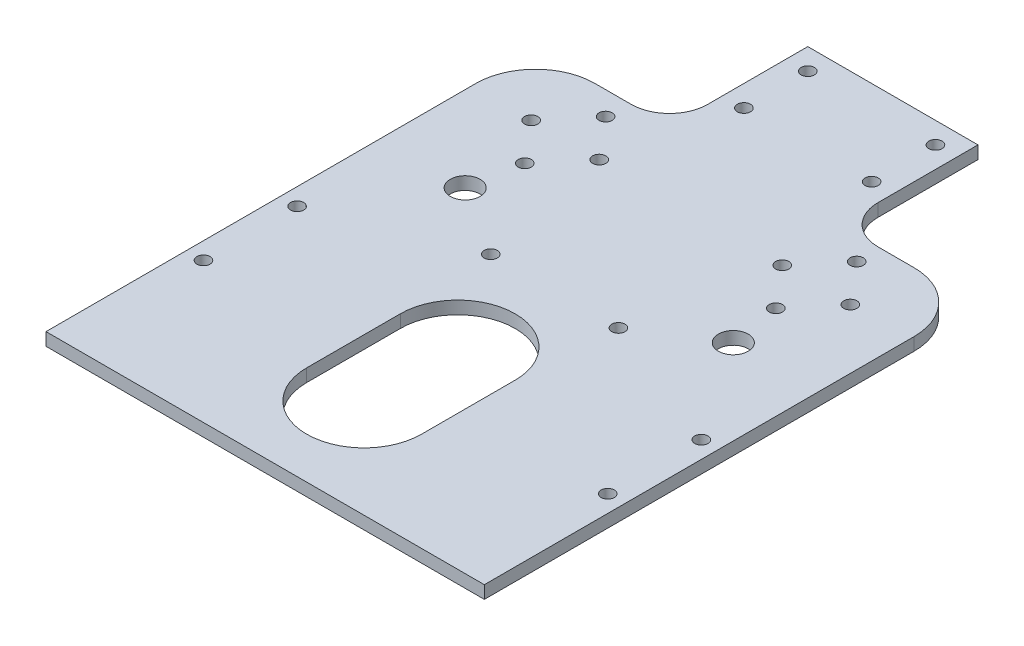
SolidWorks part; units mm, degrees
material "Hexcel AS4C (3000 丝)"
ref_plane "前视基准面" through (0, 0, 0) normal (0, 0, 1) x (1, 0, 0)
ref_plane "上视基准面" through (0, 0, 0) normal (0, 1, 0) x (1, 0, 0)
ref_plane "右视基准面" through (0, 0, 0) normal (1, 0, 0) x (0, 0, -1)
sketch "草图1" plane through (0, 0, 0) normal (0, 1, 0) x (1, 0, 0)
  line L1 (-100, 100) -> (100, 100)
  line L2 (-100, 100) -> (-100, -100)
  line L3 (-100, -100) -> (100, -100)
  line L4 (100, 100) -> (100, -100)
  line L5 (-100, 100) -> (100, -100) construction
  line L6 (-100, -100) -> (100, 100) construction
  point P0 (0, 0)
  dimension "D1" = 200
  dimension "D2" = 200
extrude "凸台-拉伸1" add sketch "草图1" along normal blind 3
sketch "草图2" plane through (0, 3, 0) normal (0, 1, 0) x (1, 0, 0)
  line L0 (0, 0) -> (0, 91) construction
  line L1 (-100, -100) -> (100, -100) construction
  line L2 (100, 100) -> (-100, 100) construction
  line L3 (-100, 0) -> (100, 0) construction
  line L5 (-100, 100) -> (-100, -100) construction
  line L6 (100, -100) -> (100, 100) construction
  line L7 (-29.5, 0) -> (29.5, 0) construction
  line L8 (-10, 100) -> (10, 100) construction
  line L9 (-10, 100) -> (-10, -100) construction
  line L10 (10, 100) -> (10, -100) construction
  line L11 (0, 0) -> (0, -29) construction
  line L13 (0, -29) -> (0, -32) construction
  circle A0 centre (-29.5, 0) radius 22.5 construction
  circle A1 centre (29.5, 0) radius 22.5 construction
  circle A2 centre (0, -29) radius 10.25 construction
  circle A3 centre (29.5, 0) radius 9.5 construction
  circle A4 centre (29.5, 0) radius 8 construction
  circle A5 centre (-29.5, 0) radius 8 construction
  circle A6 centre (-29.5, 0) radius 9.5 construction
  circle A7 centre (29.5, 9.5) radius 1.55
  circle A8 centre (21.5, 0) radius 1.55
  circle A9 centre (29.5, -9.5) radius 1.55
  circle A10 centre (37.5, 0) radius 1.55
  circle A11 centre (-29.5, -9.5) radius 1.55
  circle A12 centre (-37.5, 0) radius 1.55
  circle A13 centre (-21.5, 0) radius 1.55
  circle A14 centre (-29.5, 9.5) radius 1.55
  circle A15 centre (-15, -32) radius 1.55
  circle A16 centre (15, -32) radius 1.55
  point P16 (0, 0)
  dimension "D1" = 45
  dimension "D3" = 20.5
  dimension "D4" = 19
  dimension "D5" = 16
  dimension "D6" = 3.1
  dimension "D7" = 3.1
  dimension "D8" = 3.1
  dimension "D11" = 3.1
  dimension "D2" = 20
  dimension "D9" = 3
  dimension "D10" = 29
extrude "切除-拉伸2" cut sketch "草图2" against normal blind 10
sketch "草图4" plane through (0, 3, 0) normal (0, 1, 0) x (1, 0, 0)
  line L0 (0, 0) -> (0, 91)
  line L1 (100, 100) -> (-100, 100) construction
  line L2 (-10, 100) -> (10, 100)
  line L3 (-10, 100) -> (-10, -100) construction
  line L4 (-100, -100) -> (100, -100) construction
  line L5 (10, 100) -> (10, -100) construction
  line L6 (21.5, 0) -> (37.5, 0)
  line L7 (-29.5, 0) -> (0, 0)
  line L8 (0, -29) -> (0, 0)
  circle A0 centre (0, -29) radius 10.25
  circle A1 centre (29.5, 0) radius 8 construction
  circle A2 centre (29.5, 0) radius 9.5 construction
  circle A3 centre (29.5, 0) radius 22.5
  circle A4 centre (-29.5, 0) radius 9.5 construction
  circle A5 centre (-29.5, 0) radius 8 construction
  circle A6 centre (-29.5, 0) radius 22.5
  dimension "D1" = 20.5
  dimension "D2" = 19
  dimension "D3" = 16
  dimension "D4" = 45
sketch "草图5" plane through (0, 3, 0) normal (0, 1, 0) x (1, 0, 0)
  line L1 (-51.5, -100) -> (-51.5, 0)
  line L2 (-100, -100) -> (-51.5, -100)
  line L4 (-20, 47.5) -> (-20, 24.995)
  line L5 (51.5, -100) -> (51.5, 0)
  line L6 (51.5, -100) -> (100, -100)
  line L7 (-100, -100) -> (100, -100) construction
  line L8 (20, 47.5) -> (20, 24.995)
  line L9 (-100, -100) -> (-100, 100)
  line L10 (0, 0) -> (0, 91) construction
  line L11 (0, 47.5) -> (-20, 47.5)
  line L12 (-20, 24.995) -> (-20, 23.997)
  line L13 (0, 47.5) -> (20, 47.5)
  line L14 (-100, 100) -> (100, 100)
  line L15 (100, 100) -> (100, -100)
  line L16 (-29, 14.997) -> (-37.5, 14.997)
  line L18 (20, 24.995) -> (20, 23.997)
  line L19 (29, 14.997) -> (37.5, 14.997)
  line L20 (51.5, 0.997) -> (51.5, 0)
  line L21 (-51.5, 0.997) -> (-51.5, 0)
  arc A0 (-37.5, 14.997) -> (-51.5, 0.997) centre (-37.5, 0.997) ccw
  arc A1 (51.5, 0.997) -> (37.5, 14.997) centre (37.5, 0.997) ccw
  arc A2 (-29, 14.997) -> (-20, 23.997) centre (-29, 23.997) ccw
  arc A3 (20, 23.997) -> (29, 14.997) centre (29, 23.997) ccw
  dimension "D1" = 9
  dimension "D2" = 14
  dimension "D5" = 9
  dimension "D6" = 14
extrude "切除-拉伸3" cut sketch "草图5" against normal blind 10
sketch "草图6" plane through (0, 0, 0) normal (0, -1, 0) x (1, 0, 0)
  line L0 (20, -47.5) -> (-20, -47.5) construction
  line L7 (-20, -47.5) -> (-20, -23.997) construction
  circle A1 centre (-15, -42.5) radius 1.55
  circle A2 centre (-15, -27.5) radius 1.55
  circle A3 centre (15, -27.5) radius 1.55
  circle A4 centre (15, -42.5) radius 1.55
  dimension "D1" = 3.1
  dimension "D2" = 5
  dimension "D3" = 5
  dimension "D4" = 30
extrude "φ3.1通孔1" cut sketch "草图6" against normal blind 10
sketch "草图7" plane through (0, 3, 0) normal (0, 1, 0) x (1, 0, 0)
  line L0 (0, -29) -> (0, -14.1048) construction
  line L1 (-25.4783, -39.524) -> (-25.4783, -40.524)
  line L3 (-51.5, -100) -> (-51.5, 0.997) construction
  circle A0 centre (-47.5, -67) radius 1.55
  circle A1 centre (-47.5, -45) radius 1.55
  circle A3 centre (47.5, -67) radius 1.55
  circle A4 centre (47.5, -45) radius 1.55
  point P9 (-37.5, -39)
  dimension "D1" = 4
  dimension "D3" = 3.1
  dimension "D4" = 22
  dimension "D5" = 3.1
  dimension "D2" = 10
extrude "φ3.1通孔2" cut sketch "草图7" against normal through all contours A1 | A0 | A4 | A3
sketch "草图9" plane through (0, 3, 0) normal (0, 1, 0) x (1, 0, 0)
  line L2 (-13.5, -54.75) -> (-13.5, -76.75)
  line L3 (13.5, -54.75) -> (13.5, -76.75)
  arc A0 (13.5, -54.75) -> (-13.5, -54.75) centre (0, -54.75) ccw
  arc A1 (-13.5, -76.75) -> (13.5, -76.75) centre (0, -76.75) ccw
  dimension "D1" = 27
extrude "φ21拨单电机孔" cut sketch "草图9" against normal blind 10
sketch "草图10" plane through (0, 0, 0) normal (0, -1, 0) x (1, 0, 0)
  line L0 (-44.5, 0) -> (-44.5, 100) construction
  line L1 (0, 0) -> (0, 9.5) construction
  circle A0 centre (-31.5, 21.5) radius 3.5
  circle A1 centre (31.5, 21.5) radius 3.5
  dimension "D2" = 7
  dimension "D3" = 13
extrude "切除-拉伸6" cut sketch "草图10" against normal up to next
